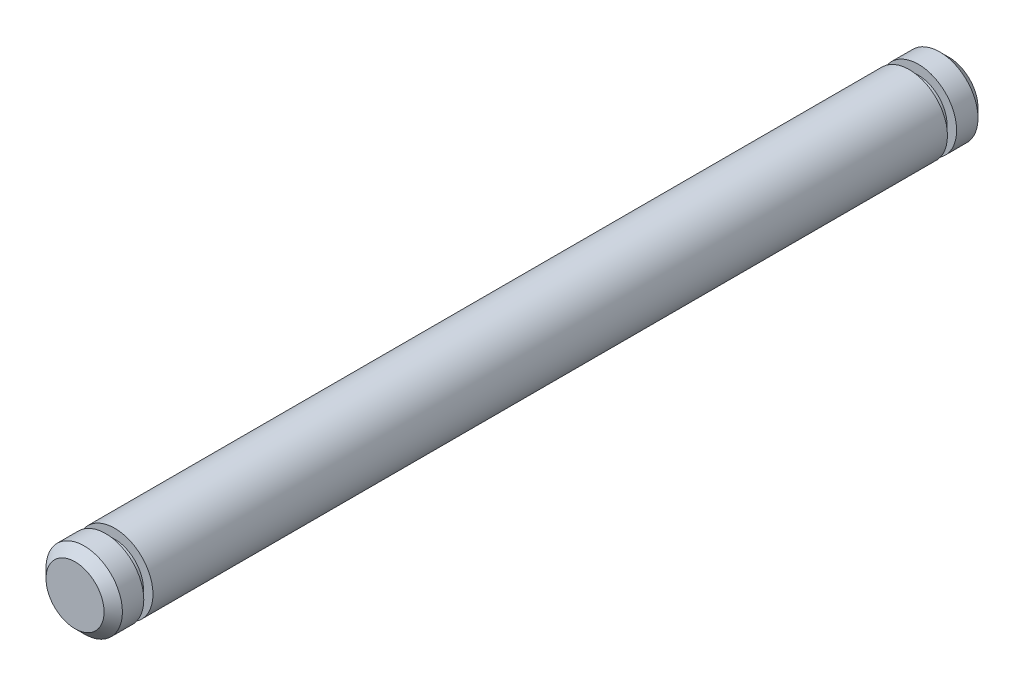
SolidWorks part; units mm, degrees
ref_plane "Front" through (0, 0, 0) normal (0, 0, 1) x (1, 0, 0)
ref_plane "Top" through (0, 0, 0) normal (0, 1, 0) x (1, 0, 0)
ref_plane "Right" through (0, 0, 0) normal (1, 0, 0) x (0, 0, -1)
sketch "Sketch1" plane through (0, 0, 0) normal (0, 0, 1) x (1, 0, 0)
  circle A0 centre (0, 0) radius 1.5875
  dimension "D1" = 3.175
extrude "Boss-Extrude1" add sketch "Sketch1" along normal mid plane 33.0149
sketch "Sketch2" plane through (0, 0, 16.5075) normal (0, 0, 1) x (1, 0, 0)
  circle A0 centre (0, 0) radius 1.1913
  dimension "D1" = 2.3825
extrude "Boss-Extrude2" add sketch "Sketch2" along normal blind 0.381
sketch "Sketch3" plane through (0, 0, 16.8885) normal (0, 0, 1) x (1, 0, 0)
  circle A0 centre (0, 0) radius 1.5875 construction
  circle A1 centre (0, 0) radius 1.5875
extrude "Boss-Extrude3" add sketch "Sketch3" along normal blind 1.27
chamfer "Chamfer1" distance 0.381 1 edges at (1.5875, 0, 18.1585)
mirror "Mirror1" about plane through (0, 0, 0) normal (0, 0, 1) of "Chamfer1", "Boss-Extrude3", "Boss-Extrude2"
